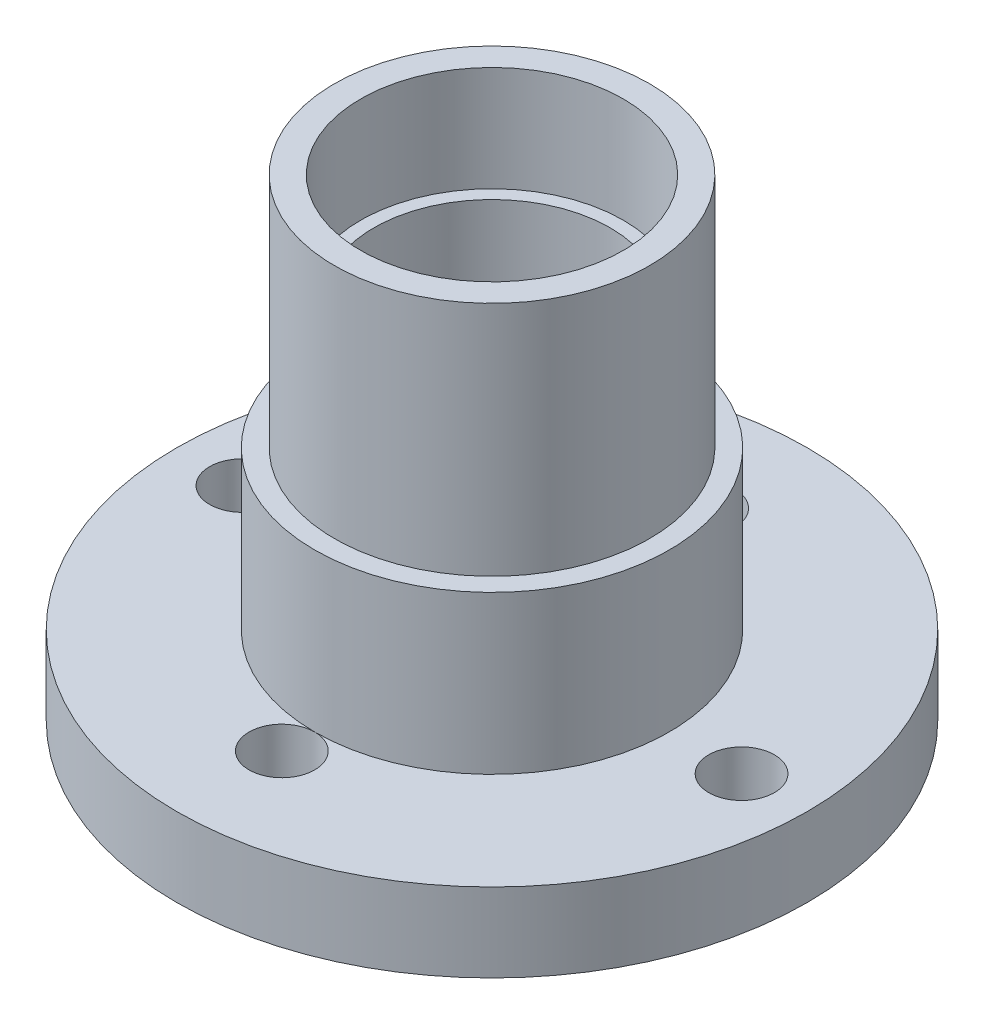
SolidWorks part; units mm, degrees
material "6061-T6 (SS)"
ref_plane "Front Plane" through (0, 0, 0) normal (0, 0, 1) x (1, 0, 0)
ref_plane "Top Plane" through (0, 0, 0) normal (0, 1, 0) x (1, 0, 0)
ref_plane "Right Plane" through (0, 0, 0) normal (1, 0, 0) x (0, 0, -1)
sketch "Sketch2" plane through (0, 0, 0) normal (0, 0, 1) x (1, 0, 0)
  line L0 (0, 0) -> (0, 24.038) construction
  line L1 (-12, 0) -> (-5, 0)
  line L2 (-5, 0) -> (-5, 4)
  line L5 (-4.5, 14) -> (-5, 14)
  line L6 (-5, 14) -> (-5, 18)
  line L7 (-5, 18) -> (-6, 18)
  line L8 (-6.75, 9) -> (-6.75, 3)
  line L9 (-6.75, 3) -> (-12, 3)
  line L10 (-12, 3) -> (-12, 0)
  line L11 (-5, 4) -> (-4.5, 4)
  line L13 (-4.5, 4) -> (-4.5, 14)
  line L14 (-6.75, 9) -> (-6, 9)
  line L15 (-6, 9) -> (-6, 18)
  dimension "D1" = 3
  dimension "D2" = 13.5
  dimension "D3" = 24
  dimension "D4" = 9
  dimension "D5" = 4
  dimension "D6" = 10
  dimension "D7" = 18
  dimension "D8" = 10
  dimension "D9" = 12
  dimension "D10" = 9
revolve "Revolve1" add sketch "Sketch2" angle 360 about L0
sketch "Sketch3" plane through (0, 0, 0) normal (0, -1, 0) x (1, 0, 0)
  line L0 (0, 12) -> (0, 0) construction
  circle A0 centre (0, 0) radius 8 construction
  circle A1 centre (0, 0) radius 9.5 construction
  circle A2 centre (0, 0) radius 12 construction
  circle A3 centre (0, 8) radius 1.25
  circle A4 centre (9.5, 0) radius 1.25
  circle A5 centre (0, -8) radius 1.25
  circle A6 centre (-9.5, 0) radius 1.25
  point P18 (0, 0)
  dimension "D2" = 2.5
  dimension "D3" = 16
  dimension "D4" = 19
  dimension "D1" = 2
extrude "Cut-Extrude1" cut sketch "Sketch3" against normal blind 6
